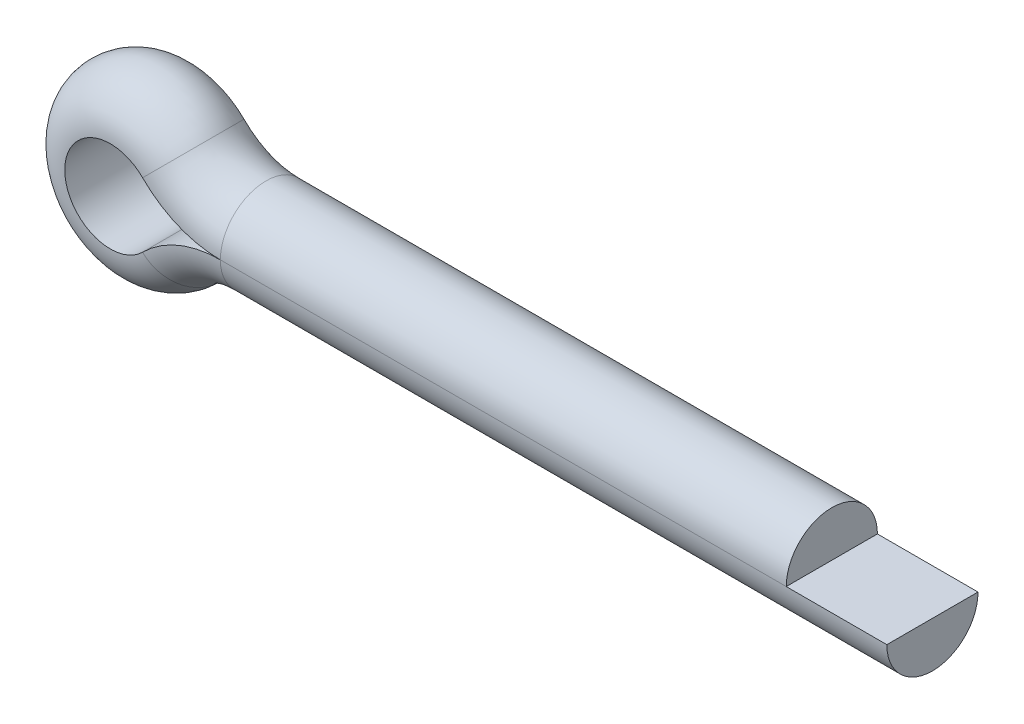
SolidWorks part; units mm, degrees
ref_plane "Front" through (0, 0, 0) normal (0, 0, 1) x (1, 0, 0)
ref_plane "Top" through (0, 0, 0) normal (0, 1, 0) x (1, 0, 0)
ref_plane "Right" through (0, 0, 0) normal (1, 0, 0) x (0, 0, -1)
other "Configuration Table"
ref_plane "Plane1" through (24.4, 0, 0) normal (1, 0, 0) x (0, 0, -1)
sketch "PathSke" plane through (1.208, 1.808, 0) normal (0, 0, 1) x (0, 1, 0)
  line L0 (-0.358, -23.192) -> (-0.358, -5.192)
  line L1 (-3.258, -5.192) -> (-3.258, -26.392)
  line L2 (-1.808, 1.208) -> (-1.808, -5.7761) construction
  arc A0 (-3.258, -5.192) -> (-3.8583, -3.7429) centre (-5.3071, -5.192) ccw
  arc A1 (-0.358, -5.192) -> (0.2424, -3.7429) centre (1.6912, -5.192) cw
  arc A3 (0.2424, -3.7429) -> (-3.8583, -3.7429) centre (-1.808, -1.692) ccw
  dimension "C" = 5.8
  dimension "d" = 2.9
  dimension "d/2" = 1.45
  dimension "a" = 3.2
  dimension "b" = 6.4
sketch "SectionSke" plane through (24.4, 0.15, 0.15) normal (1, 0, 0) x (0, 1, 0)
  line L0 (-0.15, -1.6) -> (-0.15, 1.3)
  arc A0 (-0.15, -1.6) -> (-0.15, 1.3) centre (-0.15, -0.15) ccw
  dimension "R" = 1.45
  dimension "d1" = 2.9
sweep "Body" add profiles "SectionSke" path "PathSke"
equation "\"d/2@PathSke\" = \"d@PathSke\" / 2"
equation "\"R@SectionSke\" = \"d@PathSke\" / 2"
equation "\"d1@SectionSke\" = \"d@PathSke\""
equation "\"D1@Plane1\" = \"b@PathSke\" + \"l@PathSke\""
